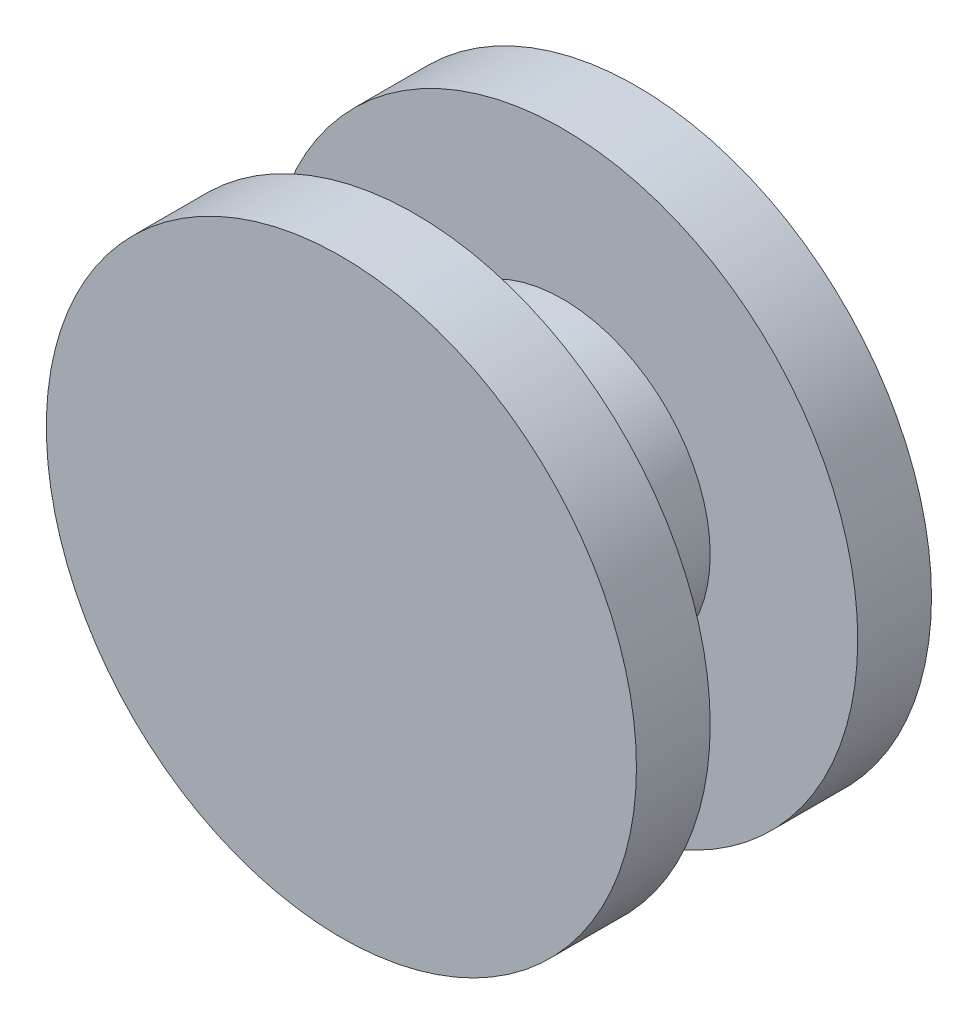
SolidWorks part; units mm, degrees
ref_plane "Front Plane" through (0, 0, 0) normal (0, 0, 1) x (1, 0, 0)
ref_plane "Top Plane" through (0, 0, 0) normal (0, 1, 0) x (1, 0, 0)
ref_plane "Right Plane" through (0, 0, 0) normal (1, 0, 0) x (0, 0, -1)
sketch "Sketch1" plane through (0, 0, 0) normal (0, 0, 1) x (1, 0, 0)
  circle A0 centre (0, 0) radius 10
extrude "Boss-Extrude1" add sketch "Sketch1" along normal blind 10
sketch "Sketch2" plane through (0, 0, 0) normal (1, 0, 0) x (0, 0, -1)
  line L0 (0, 10) -> (-10, 10) construction
  line L1 (-7.5, 10) -> (-2.5, 10)
  line L2 (-7.5, 10) -> (-7.5, 5)
  line L3 (-7.5, 5) -> (-2.5, 5)
  line L4 (-2.5, 10) -> (-2.5, 5)
  line L5 (-7.5, 10) -> (-2.5, 5) construction
  line L6 (-7.5, 5) -> (-2.5, 10) construction
  line L7 (0, -10) -> (0, 10) construction
  line L8 (-10, 0) -> (0, 0) construction
  line L9 (-10, 10) -> (-10, -10) construction
  point P0 (-5, 7.5)
  dimension "D1" = 5
  dimension "D2" = 5
  dimension "D3" = 0
  dimension "D4" = 2.5
revolve "Cut-Revolve1" cut sketch "Sketch2" angle 360 about L8
